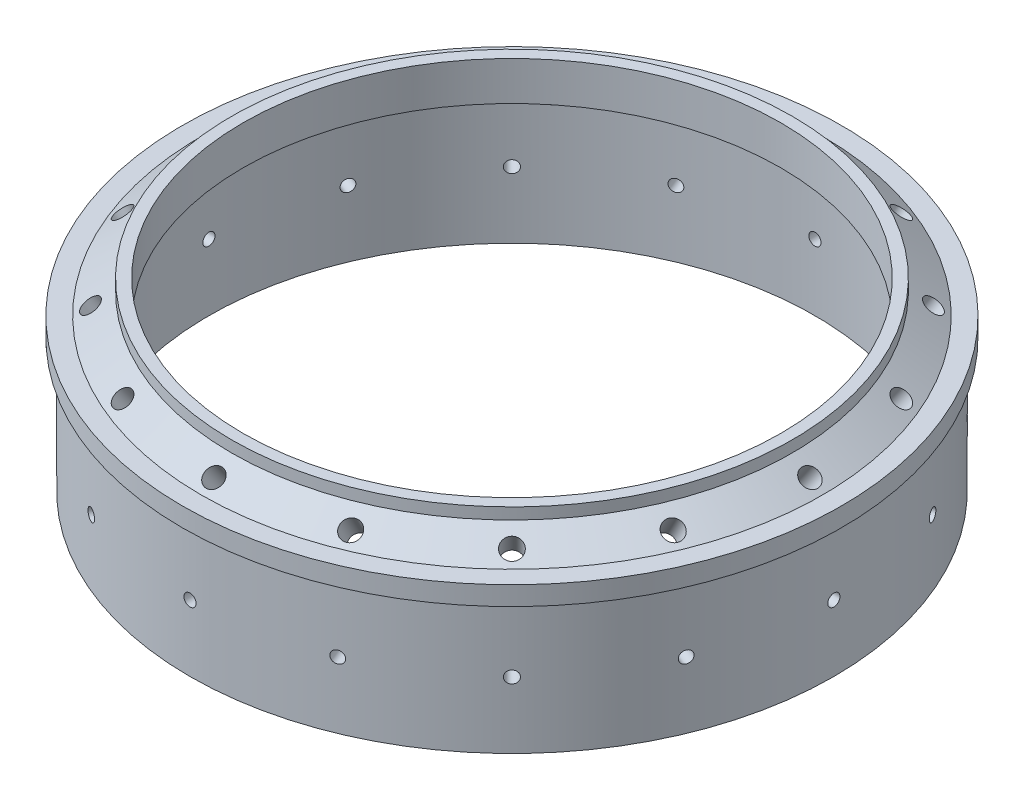
SolidWorks part; units mm, degrees
material "6063-T6"
ref_plane "Front Plane" through (0, 0, 0) normal (0, 0, 1) x (1, 0, 0)
ref_plane "Top Plane" through (0, 0, 0) normal (0, 1, 0) x (1, 0, 0)
ref_plane "Right Plane" through (0, 0, 0) normal (1, 0, 0) x (0, 0, -1)
sketch "Sketch1" plane through (0, 0, 0) normal (0, 0, 1) x (1, 0, 0)
  line L0 (0, 0) -> (-87, 0) construction
  line L1 (-87, 0) -> (-87, -4)
  line L4 (-87, -4) -> (-85, -4)
  line L5 (-85, -4) -> (-85, -39)
  line L6 (-85, -39) -> (-80, -39)
  line L9 (0, 0) -> (0, -25.8501) construction
  line L16 (-80, -7) -> (-71, -0.6981)
  line L17 (-87, 0) -> (-87, 1)
  line L18 (-87, 1) -> (-82, 1)
  line L19 (-82, 1) -> (-74, 6.6017)
  line L20 (-74, 6.6017) -> (-74, 9.6017)
  line L21 (-74, 9.6017) -> (-71, 9.6017)
  line L24 (-80, -7) -> (-80, -39)
  line L31 (-71, -7) -> (-80, -7) construction
  line L33 (-71, 9.6017) -> (-71, -0.6981)
  line L34 (-71, -0.6981) -> (-71, -7) construction
  dimension "D1" = 87
  dimension "D2" = 35
  dimension "D3" = 9
  dimension "D4" = 5
  dimension "D5" = 2
  dimension "D6" = 35
  dimension "D7" = 32
  dimension "D8" = 3
  dimension "D9" = 5
  dimension "D10" = 1
  dimension "D11" = 3
  dimension "D12" = 5
revolve "Revolve1" add sketch "Sketch1" angle 360 about L9
sketch "Sketch2" plane through (0, 0, 0) normal (0, 0, 1) x (1, 0, 0)
  line L0 (-74, 6.6017) -> (-82, 1) construction
  line L1 (-74, 6.6017) -> (-74, 1) construction
  line L2 (-74, 1) -> (-82, 1) construction
  point P4 (-78.671, 3.331)
  dimension "D1" = 4.671
hole_wizard "Ø4.2mm Dowel Hole1" positions "3DSketch1" profile "Sketch3" hole size "Ø5.0" standard "DIN" end condition up to next
sketch3d "3DSketch1"
  point P0 (-78.671, 3.331, 0)
sketch "Sketch3" plane through (-78.671, 3.331, 0) normal (0, 0, 1) x (-0.8192, -0.5736, 0)
  line L0 (0, 0) -> (0, 7.7004)
  line L1 (0, 7.7004) -> (2.5, 7.7004)
  line L2 (2.5, 7.7004) -> (2.5, 0)
  line L5 (2.5, 0) -> (0, 0)
  line L11 (0, -6.35) -> (0, 107.95) construction
  dimension "Thru Hole Dia." = 5
  dimension "Thru Hole Depth" = 7.7004
pattern_circular "CirPattern1" count 16 over 360 about axis through (0, 6.6017, 0) along (0, -1, 0) of "Ø4.2mm Dowel Hole1"
ref_plane "Plane1" through (0, 0, -85) normal (0, 0, -1) x (-1, 0, 0)
sketch "Sketch4" plane through (0, 0, -85) normal (0, 0, -1) x (-1, 0, 0)
  line L0 (-85, -39) -> (85, -39) construction
  circle A0 centre (0, -21.5) radius 1.6
  point P0 (0, -21.5)
  dimension "D2" = 3.2
  dimension "D1" = 17.5
extrude "Cut-Extrude1" cut sketch "Sketch4" against normal up to next
pattern_circular "CirPattern3" count 16 over 360 of "Cut-Extrude1"
equation "\"D1@Sketch2\"=4+cos(35)*cos(35)"
